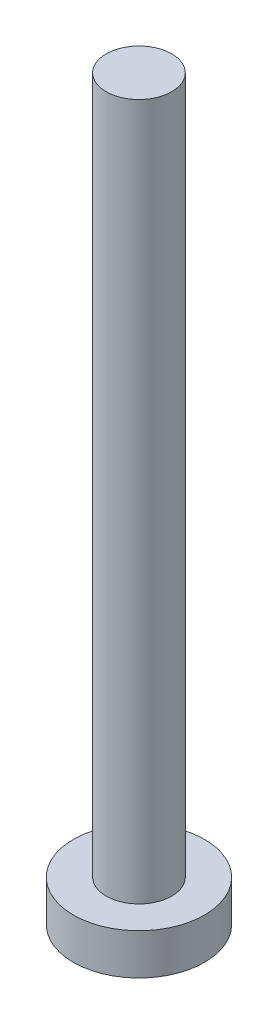
SolidWorks part; units mm, degrees
ref_plane "Front Plane" through (0, 0, 0) normal (0, 0, 1) x (1, 0, 0)
ref_plane "Top Plane" through (0, 0, 0) normal (0, 1, 0) x (1, 0, 0)
ref_plane "Right Plane" through (0, 0, 0) normal (1, 0, 0) x (0, 0, -1)
sketch "Sketch1" plane through (0, 0, 0) normal (1, 0, 0) x (0, 0, -1)
  line L0 (0, 13.7456) -> (0, -10.8954) construction
  line L1 (-4, 42.5) -> (-4, -42.5)
  line L2 (-4, -42.5) -> (-8, -42.5)
  line L3 (-8, -42.5) -> (-8, -47.5)
  line L4 (-8, -47.5) -> (0, -47.5)
  line L5 (-4, 42.5) -> (0, 42.5)
  line L6 (0, 42.5) -> (0, -47.5)
  point P5 (-4, 0)
  dimension "D1" = 5
  dimension "D2" = 8
  dimension "D3" = 85
  dimension "D4" = 16
revolve "Revolve1" add sketch "Sketch1" angle 360 about L0
thread "Thread1" pitch 2 start angle 0, offset 5, length 15, pitch 2, diameter 7.5
ref_plane "Plane1" through (-3.75, 47.5, 0) normal (0, 0, 1) x (-1, 0, 0)
sketch "Thread Profile1" plane through (-3.75, 47.5, 0) normal (0, 0, 1) x (-1, 0, 0)
  line L0 (0, 0) -> (0, 2) construction
  line L11 (0, 0) -> (0, 1.75)
  line L12 (0, 1.75) -> (-1.0825, 1.125)
  line L13 (-1.0825, 1.125) -> (-1.0825, 0.625)
  line L15 (-1.0825, 0.625) -> (0, 0)
  line L17 (-1.0825, 0.875) -> (0, 0.875) construction
  point P2 (0, 0)
  dimension "Pitch" = 2
  dimension "Profile_Angle" = 60
  dimension "Profile_Land" = 0.5
  dimension "Profile_Height" = 1.0825
sketch "Sketch5" plane through (0, -47.5, 0) normal (0, -1, 0) x (1, 0, 0)
  line L5 (-1, 1) -> (-0.2, 1) construction
  line L6 (-1, 5) -> (1, 5)
  line L27 (-1, 5) -> (-1, 1)
  line L35 (-1, -5) -> (1, -5)
  line L39 (1, 5) -> (1, 1)
  line L43 (-1, 5) -> (0, 0) construction
  line L44 (-1, -5) -> (-0.2, -1) construction
  line L45 (-5, 1) -> (-1, 1)
  line L46 (-5, 1) -> (-5, -1)
  line L47 (-5, -1) -> (-1, -1)
  line L48 (5, 1) -> (5, -1)
  line L49 (-5, 1) -> (0, 0) construction
  line L50 (-5, -1) -> (-1, -0.2) construction
  line L51 (-0.2, 1) -> (0.2, 1) construction
  line L52 (-1, 1) -> (-1, 0.2) construction
  line L53 (-1, 0.2) -> (-1, -0.2) construction
  line L54 (0.2, 1) -> (1, 1) construction
  line L55 (1, 1) -> (5, 1)
  line L56 (1, 1) -> (1, 0.2) construction
  line L57 (1, 0.2) -> (1, -0.2) construction
  line L58 (1, -0.2) -> (1, -1) construction
  line L59 (1, -1) -> (1, -5)
  line L60 (0.2, -1) -> (1, -1) construction
  line L61 (1, -1) -> (5, -1)
  line L62 (-1, -1) -> (-0.2, -1) construction
  line L63 (-0.2, -1) -> (0.2, -1) construction
  line L64 (-1, -0.2) -> (-1, -1) construction
  line L65 (-1, -1) -> (-1, -5)
  line L66 (-1, -0.2) -> (0, 0) construction
  line L67 (1, 0.2) -> (5, 1) construction
  line L68 (-0.2, -1) -> (0, 0) construction
  line L69 (0.2, 1) -> (1, 5) construction
  line L70 (0, 0) -> (0.2, -1) construction
  line L71 (0.2, -1) -> (1, -5) construction
  line L72 (0, 0) -> (1, -0.2) construction
  line L73 (1, -0.2) -> (5, -1) construction
  line L74 (0, 0) -> (0.2, 1) construction
  line L75 (0, 0) -> (1, 0.2) construction
  point P0 (0, 0)
  point P5 (0, 0)
  dimension "D1" = 10
  dimension "D2" = 2
  dimension "D3" = 2
  dimension "D4" = 10
extrude "Cut-Extrude1" cut sketch "Sketch5" against normal blind 2
